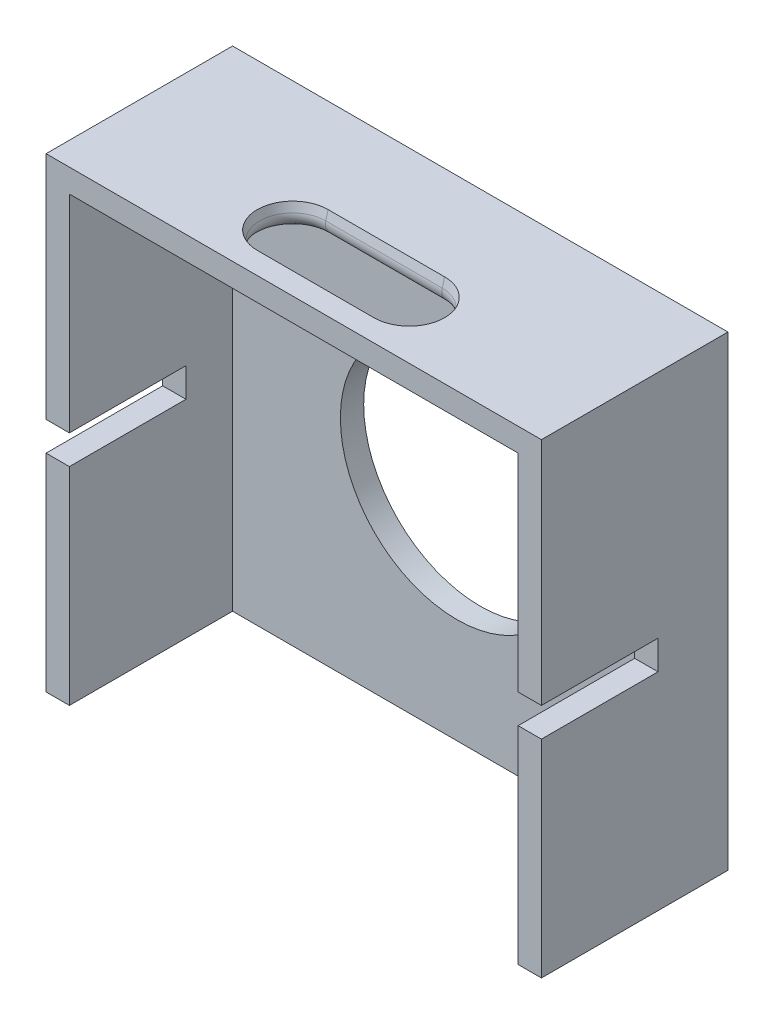
SolidWorks part; units mm, degrees
ref_plane "Front Plane" through (0, 0, 0) normal (0, 0, 1) x (1, 0, 0)
ref_plane "Top Plane" through (0, 0, 0) normal (0, 1, 0) x (1, 0, 0)
ref_plane "Right Plane" through (0, 0, 0) normal (1, 0, 0) x (0, 0, -1)
sketch "Sketch1" plane through (0, 0, 0) normal (0, 0, 1) x (1, 0, 0)
  line L1 (-19.25, 19) -> (19.25, 19)
  line L2 (-19.25, 19) -> (-19.25, -19)
  line L3 (-19.25, -19) -> (19.25, -19)
  line L4 (19.25, 19) -> (19.25, -19)
  line L5 (-19.25, 19) -> (19.25, -19) construction
  line L6 (-19.25, -19) -> (19.25, 19) construction
  circle A0 centre (0, 0) radius 10
  point P0 (0, 0)
  dimension "D3" = 20
  dimension "D1" = 38.5
  dimension "D2" = 38
extrude "Boss-Extrude1" add sketch "Sketch1" along normal blind 2
sketch "Sketch2" plane through (0, 0, 2) normal (0, 0, 1) x (1, 0, 0)
  line L0 (-19.25, -19) -> (-21.25, -19)
  line L1 (-21.25, -19) -> (-21.25, 21)
  line L2 (-21.25, 21) -> (21.25, 21)
  line L4 (19.25, -19) -> (21.25, -19)
  line L6 (19.25, -19) -> (19.25, 19)
  line L7 (19.25, 19) -> (-19.25, 19)
  line L8 (0, 40.5) -> (0, -19) construction
  line L9 (-19.25, 19) -> (-19.25, -19)
  line L10 (-19.25, -19) -> (19.25, -19) construction
  line L11 (-19.25, -19) -> (19.25, -19)
  line L12 (19.25, -19) -> (19.25, 19)
  line L13 (19.25, 19) -> (-19.25, 19)
  line L14 (-19.25, 19) -> (-19.25, -19)
  line L15 (-19.25, -19) -> (19.25, -19)
  line L16 (21.25, -19) -> (21.25, 21)
  point P10 (0, 21)
  dimension "D1" = 0
  dimension "D2" = 2
  dimension "D3" = 2
extrude "Boss-Extrude2" add sketch "Sketch2" along normal blind 14 and the other way up to surface (2 mm away) other way up to face at (10, 0, 0)
sketch "Sketch3" plane through (-19.25, 0, 0) normal (1, 0, 0) x (0, 0, -1)
  line L0 (-2, 0) -> (-16, 0) construction
  line L1 (-2, 19) -> (-2, -19) construction
  line L2 (-16, 19) -> (-16, -19) construction
  line L3 (-16, 1.25) -> (-9, 0) construction
  line L4 (-6, 1.25) -> (-16, 1.25)
  line L5 (-6, 1.25) -> (-6, -1.25)
  line L6 (-6, -1.25) -> (-16, -1.25)
  line L7 (-16, 1.25) -> (-16, -1.25)
  line L8 (-9, 0) -> (-16, -1.25) construction
  dimension "D1" = 2.5
  dimension "D2" = 4
extrude "Cut-Extrude1" cut sketch "Sketch3" against normal up to next
ref_plane "Plane1" through (0, 0, 0) normal (1, 0, 0) x (0, 0, -1)
mirror "Mirror1" about plane through (0, 0, 0) normal (1, 0, 0) of "Cut-Extrude1"
sketch "Sketch5" plane through (0, 19, 0) normal (0, -1, 0) x (1, 0, 0)
  line L0 (-5, 11.091) -> (5, 11.091) construction
  line L1 (0, -51757.809) -> (0, 51777.035) construction
  line L2 (-5, 13.591) -> (5, 13.591)
  line L3 (-5, 8.591) -> (5, 8.591)
  arc A0 (-5, 13.591) -> (-5, 8.591) centre (-5, 11.091) ccw
  arc A1 (5, 8.591) -> (5, 13.591) centre (5, 11.091) ccw
  circle A2 centre (0, 11.091) radius 1.218 construction
  point P4 (0, 11.091)
  dimension "D1" = 10
  dimension "D2" = 5
extrude "Cut-Extrude2" cut sketch "Sketch5" against normal through all draft 15 draft outward yes
fillet "Fillet1" radius 1 4 edges at (-7.5, 19, 11.091) (0, 19, 13.591) (7.5, 19, 11.091) (0, 19, 8.591)
